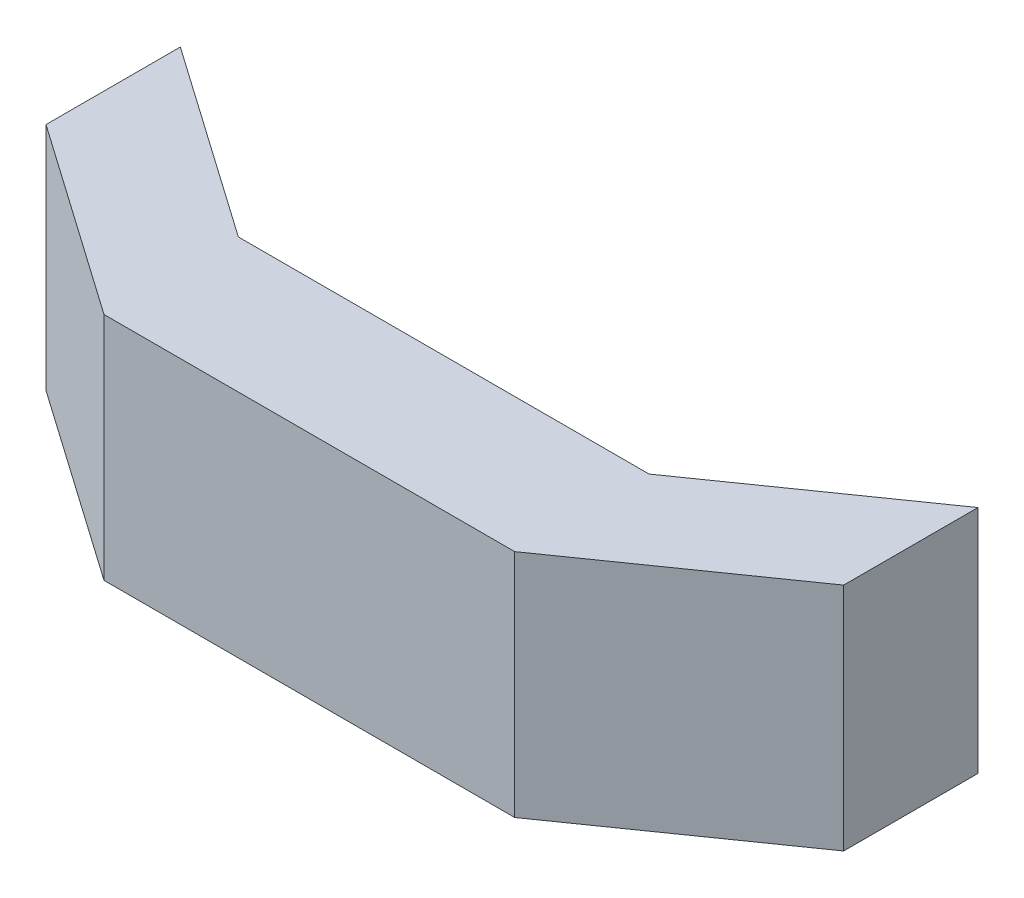
SolidWorks part; units mm, degrees
material "ABS"
ref_plane "Alzado" through (0, 0, 0) normal (0, 0, 1) x (1, 0, 0)
ref_plane "Planta" through (0, 0, 0) normal (0, 1, 0) x (1, 0, 0)
ref_plane "Vista lateral" through (0, 0, 0) normal (1, 0, 0) x (0, 0, -1)
sketch "Sketch1" plane through (0, 0, 0) normal (0, 1, 0) x (1, 0, 0)
  line L0 (-53.5, 17.5) -> (-103.911, 52.7982)
  line L1 (-53.5, -17.5) -> (53.5, -17.5)
  line L2 (-53.5, -17.5) -> (-53.5, 17.5) construction
  line L3 (-53.5, 17.5) -> (53.5, 17.5)
  line L4 (53.5, -17.5) -> (53.5, 17.5) construction
  line L5 (-53.5, -17.5) -> (53.5, 17.5) construction
  line L6 (-53.5, 17.5) -> (53.5, -17.5) construction
  line L7 (-103.911, 52.7982) -> (-103.911, 17.7982)
  line L8 (-103.911, 17.7982) -> (-53.5, -17.5)
  line L9 (0, -1856.5515) -> (0, 90971.0218) construction
  line L10 (103.911, 17.7982) -> (53.5, -17.5)
  line L11 (103.911, 52.7982) -> (103.911, 17.7982)
  line L12 (53.5, 17.5) -> (103.911, 52.7982)
  point P0 (0, 0)
  dimension "D1" = 35
  dimension "D2" = 35
  dimension "D3" = 107
extrude "Boss-Extrude1" add sketch "Sketch1" along normal blind 60
